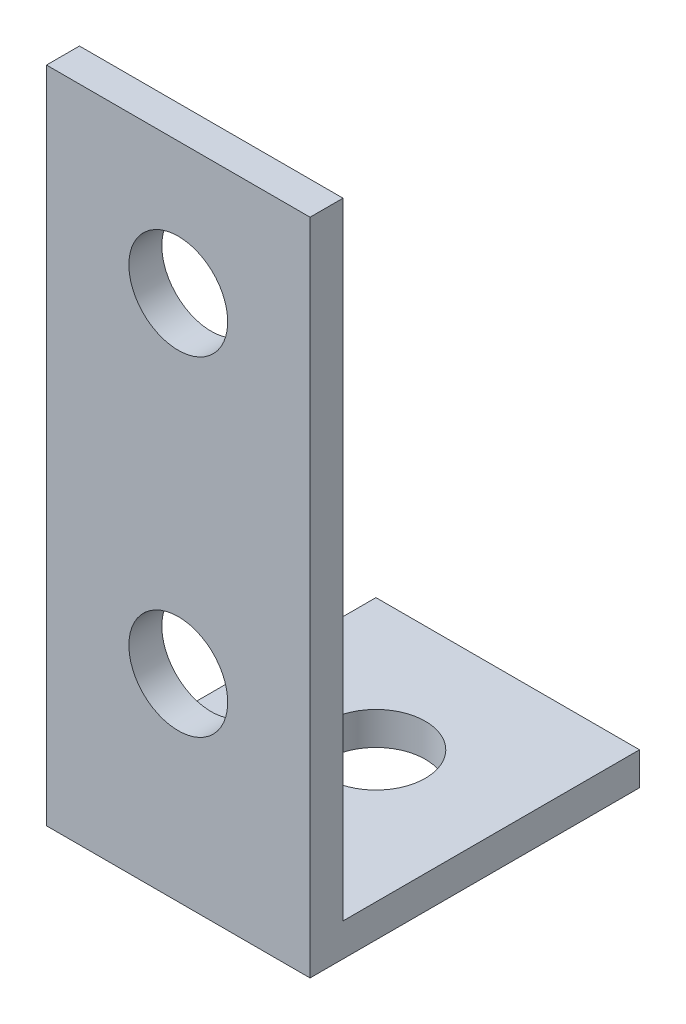
SolidWorks part; units mm, degrees
ref_plane "前视基准面" through (0, 0, 0) normal (0, 0, 1) x (1, 0, 0)
ref_plane "上视基准面" through (0, 0, 0) normal (0, 1, 0) x (1, 0, 0)
ref_plane "右视基准面" through (0, 0, 0) normal (1, 0, 0) x (0, 0, -1)
sketch "草图1" plane through (0, 0, 0) normal (1, 0, 0) x (0, 0, -1)
  line L0 (0, 0) -> (10, 0)
  line L1 (10, 0) -> (10, 1)
  line L2 (10, 1) -> (1, 1)
  line L3 (1, 1) -> (1, 20)
  line L4 (1, 20) -> (0, 20)
  line L5 (0, 20) -> (0, 0)
  dimension "D1" = 20
  dimension "D2" = 10
  dimension "D3" = 1
  dimension "D4" = 1
extrude "凸台-拉伸1" add sketch "草图1" along normal blind 8
sketch "草图2" plane through (0, 1, 0) normal (0, 1, 0) x (1, 0, 0)
  line L0 (4, 10) -> (4, 6) construction
  line L1 (8, 10) -> (0, 10) construction
  line L2 (4, 6) -> (0, 6) construction
  line L3 (0, 10) -> (0, 1) construction
  circle A0 centre (4, 6) radius 1.5
  dimension "D1" = 3
extrude "切除-拉伸1" cut sketch "草图2" against normal through all
sketch "草图3" plane through (0, 0, -1) normal (0, 0, -1) x (-1, 0, 0)
  line L0 (-4, 20) -> (-4, 16) construction
  line L1 (-8, 20) -> (0, 20) construction
  line L2 (-4, 16) -> (-4, 6) construction
  circle A0 centre (-4, 16) radius 1.5
  circle A1 centre (-4, 6) radius 1.5
  dimension "D1" = 3
  dimension "D2" = 4
  dimension "D3" = 10
extrude "切除-拉伸2" cut sketch "草图3" against normal through all
